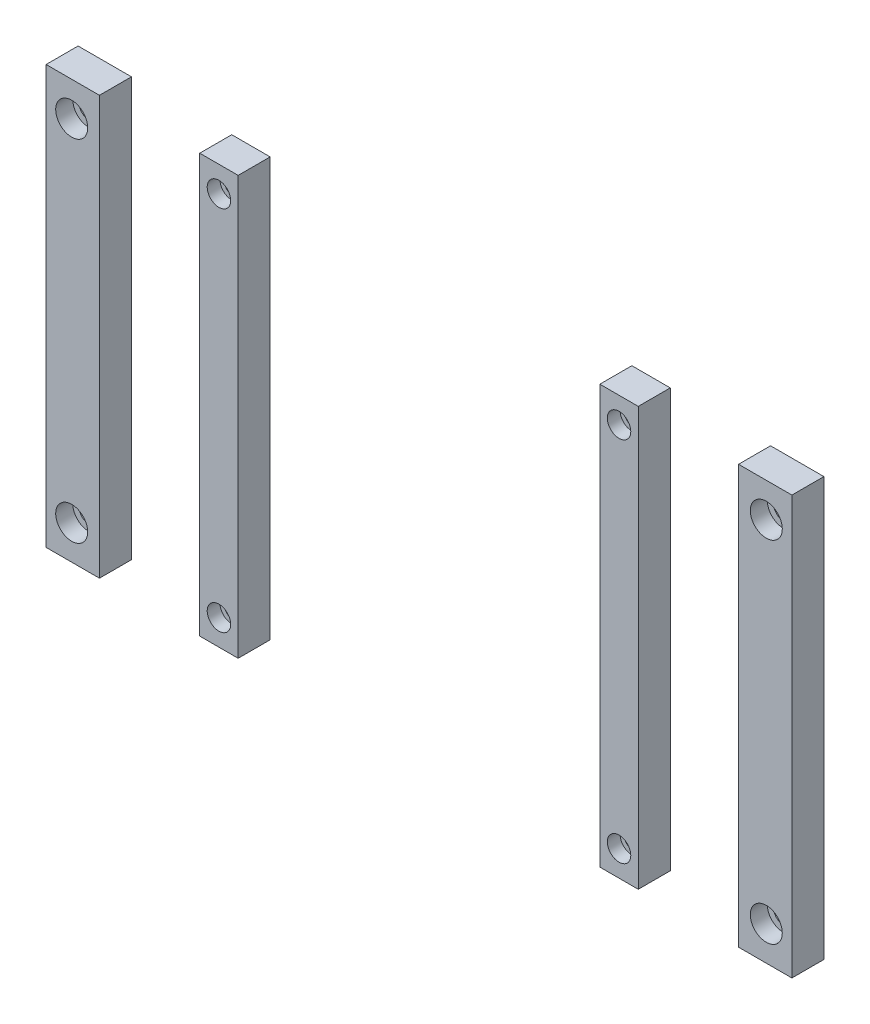
SolidWorks part; units mm, degrees
ref_plane "FP" through (0, 0, 0) normal (0, 0, 1) x (1, 0, 0)
ref_plane "TP" through (0, 0, 0) normal (0, 1, 0) x (1, 0, 0)
ref_plane "RP" through (0, 0, 0) normal (1, 0, 0) x (0, 0, -1)
sketch "Sketch1" plane through (0, 0, 0) normal (0, 0, 1) x (1, 0, 0)
  line L0 (-209.5, -98) -> (140, -98) construction
  line L1 (-119.5, -98) -> (-137.5, -98)
  line L2 (-119.5, -98) -> (-119.5, 98)
  line L3 (-119.5, 98) -> (-137.5, 98)
  line L4 (-137.5, -98) -> (-137.5, 98)
  line L5 (140, 98) -> (-209.5, 98) construction
  line L6 (-119.5, 79) -> (-119.5, -79) construction
  line L7 (-34.75, -98) -> (-34.75, 98) construction
  line L8 (115, -98) -> (115, 98)
  line L9 (-209.5, -98) -> (-184.5, -98)
  line L10 (-209.5, -98) -> (-209.5, 98)
  line L11 (-209.5, 98) -> (-184.5, 98)
  line L12 (-184.5, -98) -> (-184.5, 98)
  line L13 (140, 98) -> (115, 98)
  line L14 (140, -98) -> (140, 98)
  line L15 (140, -98) -> (115, -98)
  line L16 (68, -98) -> (68, 98)
  line L17 (50, 98) -> (68, 98)
  line L18 (50, -98) -> (50, 98)
  line L19 (50, -98) -> (68, -98)
  dimension "D1" = 18
  dimension "D2" = 25
extrude "Boss-Extrude1" add sketch "Sketch1" along normal blind 15
hole_wizard "CBORE for M6 SHCS1" positions "Sketch2" profile "Sketch3" counterbore size "M6" standard "ANSI Metric" end condition through all
sketch "Sketch2" plane through (0, 0, 15) normal (0, 0, 1) x (0.9063, 0.4226, 0)
  point P0 (89.8173, 53.008)
  point P1 (17.127, -102.8769)
sketch "Sketch3" plane through (59, 86, 15) normal (1, 0, 0) x (0, -1, 0)
  line L0 (0, 0) -> (0, 15)
  line L1 (0, 15) -> (3.3, 15)
  line L3 (3.3, 15) -> (3.3, 6)
  line L4 (3.3, 6) -> (5.5, 6)
  line L5 (5.5, 6) -> (5.5, 0)
  line L7 (5.5, 0) -> (0, 0)
  line L11 (0, -6.35) -> (0, 107.95) construction
  dimension "Thru Hole Dia." = 6.6
  dimension "Thru Hole Depth" = 15
  dimension "C'Bore Dia." = 11
  dimension "C'Bore Depth" = 6
hole_wizard "CBORE for M6 SHCS2" positions "Sketch4" profile "Sketch5" counterbore size "M6" standard "ANSI Metric" end condition through all
sketch "Sketch4" plane through (0, 0, 15) normal (0, 0, 1) x (0.9063, 0.4226, 0)
  point P0 (-80.1154, 132.2489)
  point P1 (-152.8057, -23.636)
sketch "Sketch5" plane through (-128.5, 86, 15) normal (1, 0, 0) x (0, -1, 0)
  line L0 (0, 0) -> (0, 15)
  line L1 (0, 15) -> (3.3, 15)
  line L3 (3.3, 15) -> (3.3, 6)
  line L4 (3.3, 6) -> (5.5, 6)
  line L5 (5.5, 6) -> (5.5, 0)
  line L7 (5.5, 0) -> (0, 0)
  line L11 (0, -6.35) -> (0, 107.95) construction
  dimension "Thru Hole Dia." = 6.6
  dimension "Thru Hole Depth" = 15
  dimension "C'Bore Dia." = 11
  dimension "C'Bore Depth" = 6
hole_wizard "CBORE for M8 SHCS2" positions "Sketch6" profile "Sketch7" counterbore size "M8" standard "ANSI Metric" end condition through all
sketch "Sketch6" plane through (0, 0, 15) normal (0, 0, 1) x (0.9063, 0.4226, 0)
  point P0 (81.3527, -128.4124)
  point P1 (150.6621, 20.2221)
sketch "Sketch7" plane through (128, -82, 15) normal (1, 0, 0) x (0, -1, 0)
  line L0 (0, 0) -> (0, 15)
  line L1 (0, 15) -> (4.5, 15)
  line L2 (4.5, 15) -> (4.5, 8)
  line L3 (4.5, 8) -> (7.5, 8)
  line L4 (7.5, 8) -> (7.5, 0)
  line L5 (7.5, 0) -> (0, 0)
  line L6 (0, -6.35) -> (0, 107.95) construction
  dimension "Thru Hole Dia." = 9
  dimension "Thru Hole Depth" = 15
  dimension "C'Bore Dia." = 15
  dimension "C'Bore Depth" = 8
hole_wizard "CBORE for M8 SHCS3" positions "Sketch8" profile "Sketch9" counterbore size "M8" standard "ANSI Metric" end condition through all
sketch "Sketch8" plane through (0, 0, 15) normal (0, 0, 1) x (0.9063, 0.4226, 0)
  point P0 (-144.3411, 157.7843)
  point P1 (-213.6505, 9.1499)
sketch "Sketch9" plane through (-197.5, 82, 15) normal (1, 0, 0) x (0, -1, 0)
  line L0 (0, 0) -> (0, 15)
  line L1 (0, 15) -> (4.5, 15)
  line L2 (4.5, 15) -> (4.5, 8)
  line L3 (4.5, 8) -> (7.5, 8)
  line L4 (7.5, 8) -> (7.5, 0)
  line L5 (7.5, 0) -> (0, 0)
  line L6 (0, -6.35) -> (0, 107.95) construction
  dimension "Thru Hole Dia." = 9
  dimension "Thru Hole Depth" = 15
  dimension "C'Bore Dia." = 15
  dimension "C'Bore Depth" = 8
